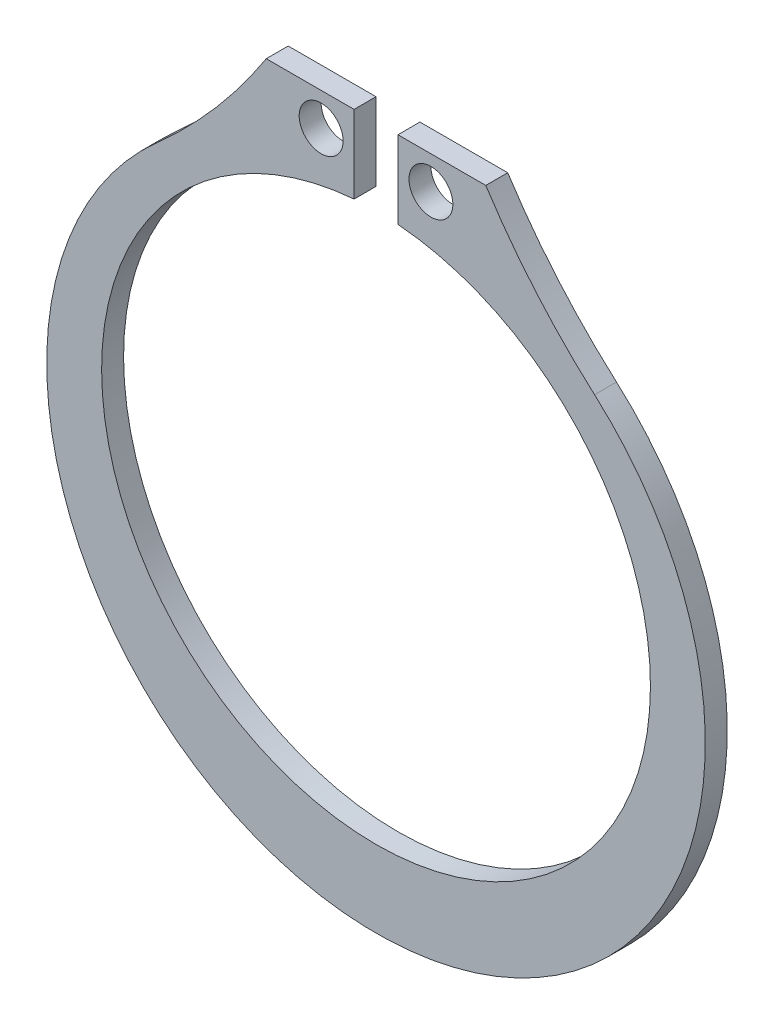
SolidWorks part; units mm, degrees
material "Alloy Steel"
ref_plane "Front Plane" through (0, 0, 0) normal (0, 0, 1) x (1, 0, 0)
ref_plane "Top Plane" through (0, 0, 0) normal (0, 1, 0) x (1, 0, 0)
ref_plane "Right Plane" through (0, 0, 0) normal (1, 0, 0) x (0, 0, -1)
sketch "Sketch1" plane through (0, 0, 0) normal (0, 0, 1) x (1, 0, 0)
  line L0 (0, 0) -> (0, 10.3048) construction
  line L1 (-5, 17) -> (-1, 17)
  line L2 (-1, 17) -> (-1, 13.4599)
  line L3 (1, 17) -> (1, 13.4599)
  line L4 (5, 17) -> (1, 17)
  arc A0 (-9.9549, 11.2205) -> (9.9549, 11.2205) centre (0, 0) ccw
  arc A2 (-1, 13.4599) -> (1, 13.4599) centre (0, 1) ccw
  arc A3 (-5, 17) -> (-9.9549, 11.2205) centre (-28.5374, 32.1655) cw
  arc A4 (5, 17) -> (9.9549, 11.2205) centre (28.5374, 32.1655) ccw
  circle A5 centre (-2.5, 15.5) radius 1
  circle A7 centre (2.5, 15.5) radius 1
  dimension "D1" = 30
  dimension "D2" = 25
  dimension "D4" = 28
  dimension "D8" = 2
  dimension "D9" = 1.5
  dimension "D3" = 1
  dimension "D5" = 16
  dimension "D6" = 10
  dimension "D7" = 2
  dimension "D10" = 1.5
extrude "Boss-Extrude1" add sketch "Sketch1" along normal blind 1
